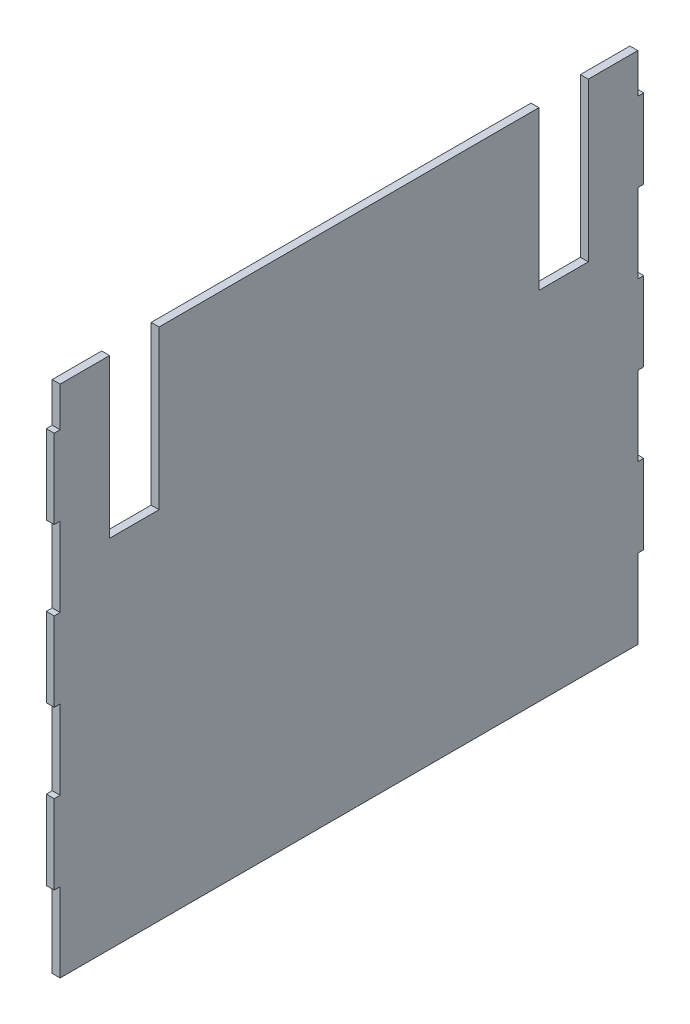
SolidWorks part; units mm, degrees
ref_plane "Front Plane" through (0, 0, 0) normal (0, 0, 1) x (1, 0, 0)
ref_plane "Top Plane" through (0, 0, 0) normal (0, 1, 0) x (1, 0, 0)
ref_plane "Right Plane" through (0, 0, 0) normal (1, 0, 0) x (0, 0, -1)
sketch "Sketch1" plane through (0, 0, 0) normal (1, 0, 0) x (0, 0, -1)
  line L1 (-282.9871, 143.2232) -> (-257.9871, 143.2232)
  line L3 (-282.9871, -116.7768) -> (9.0129, -116.7768)
  line L5 (-136.9871, 143.2232) -> (-136.9871, -116.7768) construction
  line L38 (-285.9871, 123.2232) -> (-285.9871, -108.1506) construction
  line L39 (-282.9871, 143.2232) -> (-282.9871, 123.2232)
  line L40 (-282.9871, 123.2232) -> (-285.9871, 123.2232)
  line L41 (-285.9871, 123.2232) -> (-285.9871, 83.2232)
  line L42 (-285.9871, 83.2232) -> (-282.9871, 83.2232)
  line L43 (-282.9871, 83.2232) -> (-282.9871, 43.2232)
  line L44 (-282.9871, 43.2232) -> (-285.9871, 43.2232)
  line L45 (-285.9871, 43.2232) -> (-285.9871, 3.2232)
  line L46 (-285.9871, 3.2232) -> (-282.9871, 3.2232)
  line L47 (-282.9871, 3.2232) -> (-282.9871, -36.7768)
  line L48 (-282.9871, -36.7768) -> (-285.9871, -36.7768)
  line L49 (-285.9871, -36.7768) -> (-285.9871, -76.7768)
  line L50 (-285.9871, -76.7768) -> (-282.9871, -76.7768)
  line L51 (-282.9871, -76.7768) -> (-282.9871, -116.7768)
  line L52 (-232.9871, 143.2232) -> (-40.9871, 143.2232)
  line L67 (-257.9871, 143.2232) -> (-257.9871, 63.2232)
  line L68 (-257.9871, 63.2232) -> (-232.9871, 63.2232)
  line L69 (-232.9871, 143.2232) -> (-232.9871, 63.2232)
  line L70 (12.0129, 123.2232) -> (12.0129, -108.1506) construction
  line L71 (-40.9871, 143.2232) -> (-40.9871, 63.2232)
  line L72 (-15.9871, 63.2232) -> (-40.9871, 63.2232)
  line L73 (-15.9871, 143.2232) -> (-15.9871, 63.2232)
  line L74 (9.0129, -76.7768) -> (9.0129, -116.7768)
  line L75 (12.0129, -76.7768) -> (9.0129, -76.7768)
  line L76 (12.0129, -36.7768) -> (12.0129, -76.7768)
  line L77 (9.0129, -36.7768) -> (12.0129, -36.7768)
  line L78 (9.0129, 3.2232) -> (9.0129, -36.7768)
  line L79 (12.0129, 3.2232) -> (9.0129, 3.2232)
  line L80 (12.0129, 43.2232) -> (12.0129, 3.2232)
  line L81 (9.0129, 43.2232) -> (12.0129, 43.2232)
  line L82 (9.0129, 83.2232) -> (9.0129, 43.2232)
  line L83 (12.0129, 83.2232) -> (9.0129, 83.2232)
  line L84 (12.0129, 123.2232) -> (12.0129, 83.2232)
  line L85 (9.0129, 123.2232) -> (12.0129, 123.2232)
  line L86 (9.0129, 143.2232) -> (9.0129, 123.2232)
  line L87 (9.0129, 143.2232) -> (-15.9871, 143.2232)
  dimension "D2" = 3
  dimension "D3" = 3
  dimension "D4" = 3
  dimension "D5" = 3
  dimension "D6" = 20
  dimension "D7" = 40
  dimension "D8" = 25
  dimension "D9" = 40
  dimension "D10" = 40
  dimension "D11" = 80
  dimension "D12" = 25
  dimension "D13" = 292
  dimension "D14" = 149
  dimension "D15" = 192
extrude "Boss-Extrude1" add sketch "Sketch1" along normal blind 4
